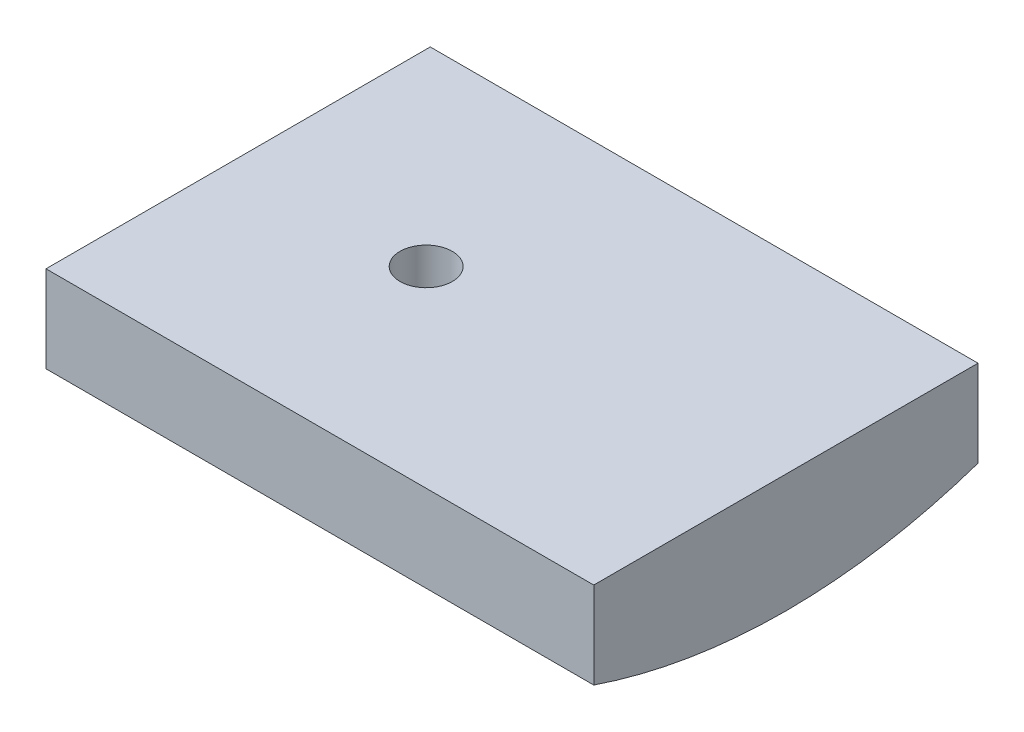
SolidWorks part; units mm, degrees
ref_plane "Front Plane" through (0, 0, 0) normal (0, 0, 1) x (1, 0, 0)
ref_plane "Top Plane" through (0, 0, 0) normal (0, 1, 0) x (1, 0, 0)
ref_plane "Right Plane" through (0, 0, 0) normal (1, 0, 0) x (0, 0, -1)
sketch "Sketch1" plane through (0, 0, 0) normal (1, 0, 0) x (0, 0, -1)
  line L0 (0, 0) -> (0, -90.5205) construction
  line L1 (-23.5, -58.2) -> (23.5, -58.2)
  line L2 (-23.5, -58.2) -> (-23.5, -68.7971)
  line L4 (23.5, -58.2) -> (23.5, -68.7971)
  arc A0 (-23.5, -68.7971) -> (23.5, -68.7971) centre (0, 0) ccw construction
  arc A1 (-23.5, -68.7971) -> (23.5, -68.7971) centre (0, 0) ccw
  circle A2 centre (0, 0) radius 72.7 construction
  point P7 (0, -72.7)
  dimension "D1" = 145.4
  dimension "D2" = 14.5
  dimension "D3" = 47
extrude "Boss-Extrude1" add sketch "Sketch1" along normal blind 67
sketch "Sketch2" plane through (0, -58.2, 0) normal (0, 1, 0) x (1, 0, 0)
  line L0 (0, 23.5) -> (67, -23.5) construction
  line L1 (0, -23.5) -> (67, 23.5) construction
  line L2 (23, 0) -> (33.5, 0) construction
  line L4 (67, 23.5) -> (67, -23.5) construction
  circle A0 centre (23, 0) radius 3.2
  dimension "D1" = 6.4
  dimension "D2" = 44
extrude "Cut-Extrude1" cut sketch "Sketch2" against normal through all
